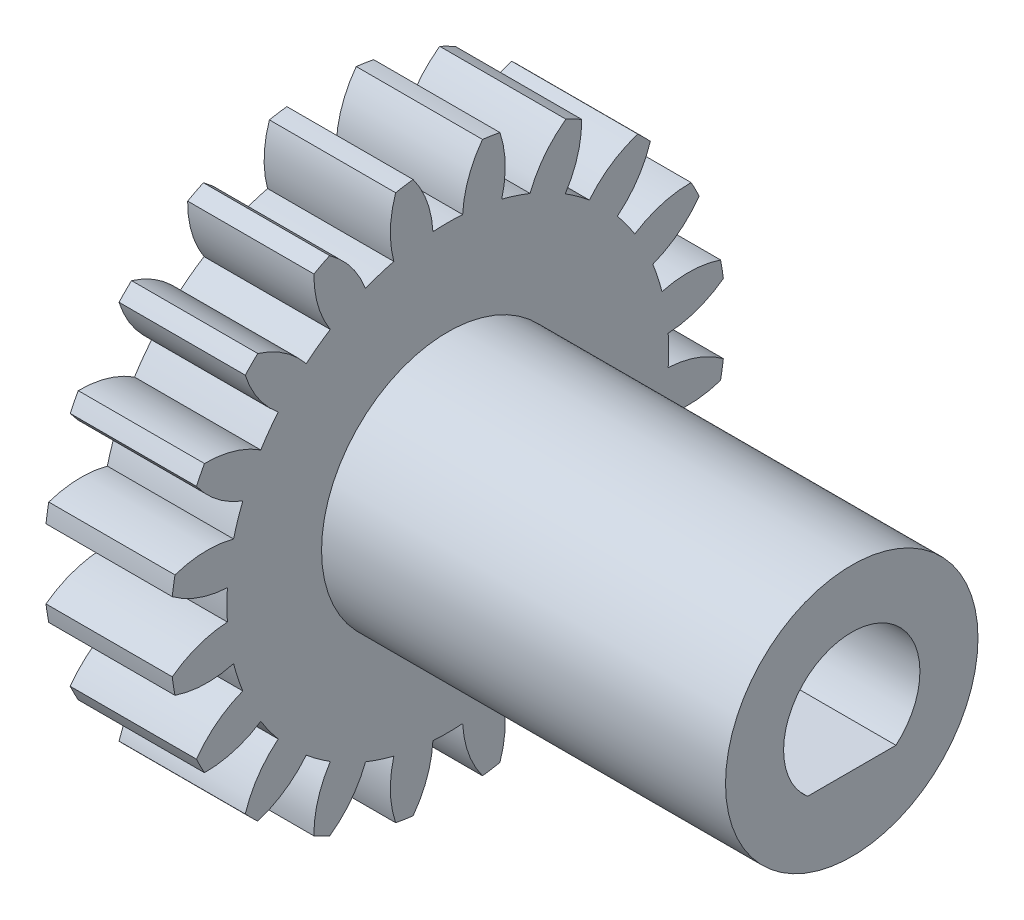
SolidWorks part; units mm, degrees
ref_plane "Plane1" through (0, 0, 0) normal (0, 0, 1) x (1, 0, 0)
ref_plane "Plane2" through (0, 0, 0) normal (0, 1, 0) x (1, 0, 0)
ref_plane "Plane3" through (0, 0, 0) normal (1, 0, 0) x (0, 0, -1)
sketch "HoldingSke" plane through (0, 0, 0) normal (0, 1, 0) x (1, 0, 0)
  line L0 (0, 0) -> (0.9397, -0.342)
  line L1 (-15, 0) -> (100, 0) construction
  line L2 (0, 0) -> (-2.1039, 2.3779)
  line L3 (0, 0) -> (-11.863, 4.5341)
  line L4 (0, 0) -> (8.1152, 2.9537)
  line L5 (0, 0) -> (-46.8476, -17.4728)
  line L6 (0, 0) -> (-4.1448, -2.7965)
  line L7 (-2.1039, 2.3779) -> (8.6586, 51.2059)
  line L8 (-76.2, 54.61) -> (-75.3, 54.61)
  line L9 (-67.7845, 28.3722) -> (-49.3413, 33.142)
  line L10 (-76.2, 71.12) -> (104.1128, 71.12)
  line L11 (0, 0) -> (-5, 0)
  line L12 (-76.2, 101.6) -> (-76.162, 101.6)
  line L13 (24.9733, 27.94) -> (52.9518, 28.4284)
  line L14 (24.9733, 27.94) -> (24.9743, 27.94)
  line L15 (24.9733, 27.94) -> (100.4006, 29.5858)
  line L16 (-63.627, -1) -> (-12.827, -1)
  circle A0 centre (0, 0) radius 2.5
  circle A1 centre (0, 0) radius 8.749
  circle A2 centre (0, 0) radius 37.5
  circle A3 centre (0, 0) radius 2.5
  dimension "MHD" = 17.498
  dimension "Hub_dia" = 75
  dimension "Bore" = 5
  dimension "MBD" = 5
  dimension "Num_teeth" = 20
  dimension "Pitch" = 1
  dimension "Overall_len" = 50
  dimension "Show_teeth" = 20
  dimension "Thickness" = 5
  dimension "OAL" = 50.0001
  dimension "T_dim" = 0.9
  dimension "Ap" = 14.5
  dimension "H" = 19.05
  dimension "Pitch_radius" = 180.3128
  dimension "Width" = 5
  dimension "Backlash" = 0.038
  dimension "Addendum_fac" = 1
  dimension "Dedendum_fac" = 1.25
  dimension "Clearance_fac" = 0.25
  dimension "Dedendum_add" = 0.001
  dimension "Module" = 1
sketch "BasProSke" plane through (0, 0, 0) normal (0, 1, 0) x (1, 0, 0)
  line L0 (-10, 0) -> (60, 0) construction
  line L1 (0, 0) -> (0, 11)
  line L2 (0, 0) -> (5, 0)
  line L3 (5, 0) -> (5, 11)
  line L4 (5, 11) -> (0, 11)
  dimension "Thickness" = 5
  dimension "Diameter" = 22
revolve "Base-Revolve" add sketch "BasProSke" angle 360 about L0
sketch "TooCutSke" plane through (0, 0, 0) normal (1, 0, 0) x (0, 0, -1)
  line L1 (0, 0) -> (0, 107) construction
  line L2 (0, 0) -> (-0.8511, 9.9637) construction
  line L3 (0, 0) -> (-3.1206, 19.7028) construction
  line L4 (-0.8511, 9.9637) -> (-1.5603, 9.8514) construction
  arc A0 (0.5894, 8.7291) -> (-0.5894, 8.7291) centre (0, 0) ccw
  arc A1 (1.3917, 10.9372) -> (-1.3917, 10.9372) centre (0, 0) ccw
  circle A2 centre (0, 0) radius 10 construction
  circle A3 centre (0, 0) radius 9.6815 construction
  arc A4 (-0.5894, 8.7291) -> (-1.3917, 10.9372) centre (-4.5843, 8.5273) ccw
  arc A5 (1.3917, 10.9372) -> (0.5894, 8.7291) centre (4.5843, 8.5273) ccw
  dimension "Root_dia" = 17.498
  dimension "Overcut_dia" = 22.0508
  dimension "Pitch_dia" = 20
  dimension "Base_dia" = 19.363
  dimension "Flank_rad" = 4
  dimension "Half_ang" = 9
  dimension "Half_CT" = 0.7181
extrude "ToothCut" cut sketch "TooCutSke" along normal through all
fillet "Breaks" [suppressed] radius 0.02
fillet "RootFillets" [suppressed] radius 0.251
pattern_circular "TeethCuts" count 20 every 18 about axis through (-10, 0, 0) along (1, 0, 0) of "ToothCut", "RootFillets", "Breaks"
sketch "HubNeaOneSke" plane through (0, 0, 0) normal (-1, 0, 0) x (0, 0, 1)
  circle A0 centre (0, 0) radius 8.749
  dimension "Diameter" = 17.498
extrude "HubNearOne" [suppressed] add sketch "HubNeaOneSke" along normal blind 45.0001
sketch "HubNeaBotSke" plane through (0, 0, 0) normal (-1, 0, 0) x (0, 0, 1)
  circle A0 centre (0, 0) radius 8.749
  dimension "Diameter" = 17.498
extrude "HubNearBoth" [suppressed] add sketch "HubNeaBotSke" along normal blind 22.5
ref_plane "FarPln" through (5, 0, 0) normal (1, 0, 0) x (0, 0, -1)
sketch "HubFarSke" plane through (5, 0, 0) normal (1, 0, 0) x (0, 0, -1)
  circle A0 centre (0, 0) radius 8.749
  dimension "Diameter" = 17.498
extrude "HubFar" [suppressed] add sketch "HubFarSke" along normal blind 22.5
sketch "BorSke" plane through (0, 0, 0) normal (1, 0, 0) x (0, 0, -1)
  circle A0 centre (0, 0) radius 2.5
  dimension "Diameter" = 5
extrude "Bore" cut sketch "BorSke" along normal mid plane 100.0001
sketch "KeySke" plane through (0, 0, 0) normal (1, 0, 0) x (0, 0, -1)
  line L0 (-1, 0) -> (-1, 3.4)
  line L1 (-1, 3.4) -> (1, 3.4)
  line L2 (1, 3.4) -> (1, 0)
  line L3 (0, 0) -> (0, 34) construction
  line L4 (-1, 0) -> (1, 0)
  dimension "Offset" = 3.4
  dimension "Width" = 2
extrude "Keyway" [suppressed] cut sketch "KeySke" along normal mid plane 100.0001
pattern_circular "Keyway2" [suppressed] count 2 every 90 about axis through (-10, 0, 0) along (1, 0, 0)
sketch "Sketch1" plane through (5, 0, 0) normal (1, 0, 0) x (0, 0, -1)
  circle A0 centre (0, 0) radius 5
  dimension "D1" = 10
extrude "Boss-Extrude2" add sketch "Sketch1" along normal blind 16 and the other way through all
sketch "Sketch2" plane through (21, 0, 0) normal (1, 0, 0) x (0, 0, -1)
  line L0 (-1.75, -2.0561) -> (1.75, -2.0561)
  circle A0 centre (0, 0) radius 2.7
  dimension "D1" = 5.4
  dimension "D2" = 3.5
extrude "Cut-Extrude1" cut sketch "Sketch2" against normal through all contours L0 A0
equation "' \"Module@HoldingSke\" = 6.35"
equation "' \"Num_teeth@HoldingSke\" = 12"
equation "' \"Ap@HoldingSke\" =  20"
equation "' \"Ap@HoldingSke\" = 20"
equation "' \"Width@HoldingSke\" = 0.5 * 25.4"
equation "' \"Hub_dia@HoldingSke\"= 1 * 25.4"
equation "' \"Hub_dia@HoldingSke\" = 1 * 25.4"
equation "' \"Overall_len@HoldingSke\" = 1.0 * 25.4"
equation "' \"Bore@HoldingSke\" = 0.75 * 25.4"
equation "' \"T_dim@HoldingSke\" = 0.1 * 25.4"
equation "' \"Width@KeySke\" = 0.25 * 25.4"
equation "' \"Show_teeth@HoldingSke\" = 13"
equation "' \"Backlash@HoldingSke\" = 0.009 * 25.4"
equation "' \"Addendum_fac@HoldingSke\" = 1.0"
equation "' \"Dedendum_fac@HoldingSke\" = 1.25"
equation "' \"Dedendum_add@HoldingSke\" = 0.00005 * 25.4"
equation "' \"Clearance_fac@HoldingSke\" = 0.25"
equation "\"Pitch@HoldingSke\" = 1 / \"Module@HoldingSke\""
equation "\"Overcut_dia@TooCutSke\" = (\"Num_teeth@HoldingSke\" + 2 * \"Addendum_fac@HoldingSke\") / \"Pitch@HoldingSke\" + 0.002 * 25.4"
equation "\"Pitch_dia@TooCutSke\" = \"Num_teeth@HoldingSke\" / \"Pitch@HoldingSke\""
equation "\"Base_dia@TooCutSke\" = \"Num_teeth@HoldingSke\" / \"Pitch@HoldingSke\" * cos((\"Ap@HoldingSke\"  * 3.14159265 / 180))"
equation "\"Root_dia@TooCutSke\" = (\"Num_teeth@HoldingSke\" + 2) / \"Pitch@HoldingSke\" - 2 * (\"Addendum_fac@HoldingSke\" + \"Dedendum_fac@HoldingSke\") / \"Pitch@HoldingSke\" - \"Dedendum_add@HoldingSke\" * 2"
equation "\"Half_ang@TooCutSke\" = 180 / \"Num_teeth@HoldingSke\""
equation "\"Half_CT@TooCutSke\" = \"Num_teeth@HoldingSke\" / \"Pitch@HoldingSke\" * sin((3.14159265 / 2 / \"Num_teeth@HoldingSke\")) / 2 - 7 * \"Backlash@HoldingSke\" / 4"
equation "\"Flank_rad@TooCutSke\" = \"Num_teeth@HoldingSke\" / \"Pitch@HoldingSke\" / 5"
equation "\"Radius@RootFillets\" = \"Clearance_fac@HoldingSke\" / \"Pitch@HoldingSke\" + \"Dedendum_add@HoldingSke\""
equation "\"Break_rad@Breaks\" = 0.02 / \"Pitch@HoldingSke\""
equation "\"Thickness@HoldingSke\" = \"Width@HoldingSke\""
equation "\"OAL@HoldingSke\" = \"Thickness@HoldingSke\""
equation "\"MHD@HoldingSke\" = (\"Num_teeth@HoldingSke\" + 2) / \"Pitch@HoldingSke\" - 2 * (\"Addendum_fac@HoldingSke\" + \"Dedendum_fac@HoldingSke\")  / \"Pitch@HoldingSke\" - \"Dedendum_add@HoldingSke\" * 2"
equation "\"MBD@HoldingSke\" = (\"Num_teeth@HoldingSke\" + 2) / \"Pitch@HoldingSke\" - 2 * (\"Addendum_fac@HoldingSke\" + \"Dedendum_fac@HoldingSke\")  / \"Pitch@HoldingSke\" - \"Dedendum_add@HoldingSke\" * 2 - 0.002 * 25.4"
equation "\"MHD@HoldingSke\" = ((sgn( \"MHD@HoldingSke\" - \"Hub_dia@HoldingSke\" )-1)*( \"MHD@HoldingSke\" - \"Hub_dia@HoldingSke\" ))/-2+ \"Hub_dia@HoldingSke\""
equation "\"MBD@HoldingSke\" = ((sgn( \"MBD@HoldingSke\" - \"Bore@HoldingSke\" )-1)*( \"MBD@HoldingSke\" - \"Bore@HoldingSke\" ))/-2+ \"Bore@HoldingSke\""
equation "\"OAL@HoldingSke\" = ((sgn( \"OAL@HoldingSke\" - \"Overall_len@HoldingSke\" )+1)*( \"OAL@HoldingSke\" - \"Overall_len@HoldingSke\" ))/2 + \"Overall_len@HoldingSke\" + 0.000002 * 25.4"
equation "\"Num_teeth@TeethCuts\" = int( \"Show_teeth@HoldingSke\" ) + 1"
equation "\"Num_teeth@TeethCuts\" = ((sgn( \"Num_teeth@TeethCuts\" - \"Num_teeth@HoldingSke\" )-1)*( \"Num_teeth@TeethCuts\" - \"Num_teeth@HoldingSke\" ))/-2+ \"Num_teeth@HoldingSke\""
equation "\"Num_teeth@TeethCuts\" = ((sgn( \"Num_teeth@TeethCuts\" - 2.0)+1)*( \"Num_teeth@TeethCuts\" - 2.0))/2 +2.0"
equation "\"Angle@TeethCuts\" = 360.0 / \"Num_teeth@HoldingSke\""
equation "\"Diameter@BasProSke\" = (\"Num_teeth@HoldingSke\" + 2 * \"Addendum_fac@HoldingSke\") / \"Pitch@HoldingSke\""
equation "\"Thickness@BasProSke\"  = \"Thickness@HoldingSke\""
equation "' \"Fillet_rad@BasProSke\" =  \"Thickness@HoldingSke\" * 0.05"
equation "' \"Fillet_rad@BasProSke\" = \"Thickness@HoldingSke\" * 0.05"
equation "\"MHD@HoldingSke\" = ((sgn( \"MHD@HoldingSke\" - \"Root_dia@TooCutSke\" )-1)*( \"MHD@HoldingSke\" - \"Root_dia@TooCutSke\" ))/-2+ \"Root_dia@TooCutSke\""
equation "\"Diameter@HubNeaOneSke\" = \"MHD@HoldingSke\""
equation "\"Length@HubNearOne\" = \"OAL@HoldingSke\" - \"Thickness@BasProSke\""
equation "\"Diameter@HubNeaBotSke\" = \"MHD@HoldingSke\""
equation "\"Length@HubNearBoth\" = ( \"OAL@HoldingSke\" - \"Thickness@BasProSke\" ) / 2.0"
equation "\"Thickness@FarPln\" = \"Thickness@BasProSke\""
equation "\"Diameter@HubFarSke\" = \"MHD@HoldingSke\""
equation "\"Length@HubFar\" = ( \"OAL@HoldingSke\" - \"Thickness@BasProSke\" ) / 2.0"
equation "\"Diameter@BorSke\" = \"MBD@HoldingSke\""
equation "\"D1@Bore\" = \"OAL@HoldingSke\" * 2.0"
equation "\"D1@Keyway\" = \"OAL@HoldingSke\" * 2.0"
equation "\"Offset@KeySke\" = \"T_dim@HoldingSke\" + \"MBD@HoldingSke\" / 2.0"
